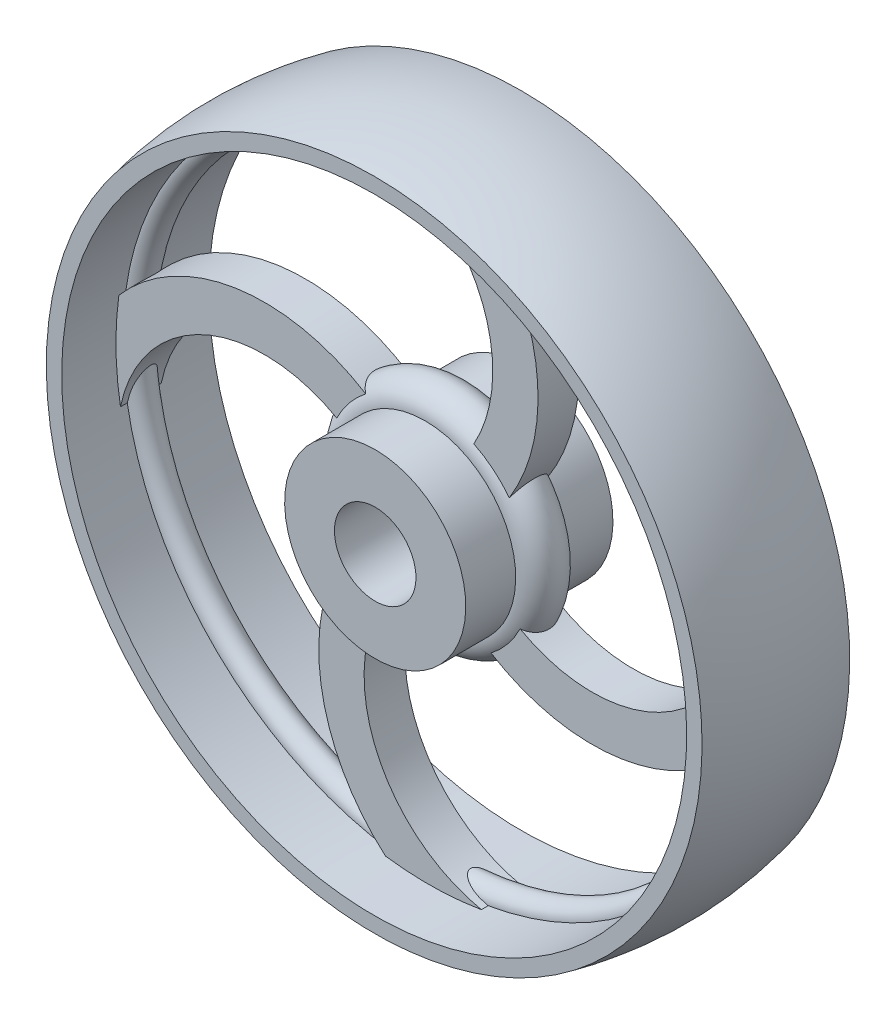
SolidWorks part; units mm, degrees
ref_plane "Front Plane" through (0, 0, 0) normal (0, 0, 1) x (1, 0, 0)
ref_plane "Top Plane" through (0, 0, 0) normal (0, 1, 0) x (1, 0, 0)
ref_plane "Right Plane" through (0, 0, 0) normal (1, 0, 0) x (0, 0, -1)
sketch "Sketch1" plane through (0, 0, 0) normal (0, 0, 1) x (1, 0, 0)
  circle A0 centre (0, 0) radius 145
  dimension "D1" = 290
sketch "Sketch2" plane through (0, 0, 0) normal (1, 0, 0) x (0, 0, -1)
  line L0 (5.9992, 138) -> (32.0507, 138)
  line L2 (-32.9493, 144.7985) -> (-32.9493, 138)
  line L3 (-32.9493, 138) -> (-5.9992, 138)
  line L4 (32.0507, 145) -> (32.0507, 138)
  line L5 (-54.2193, 131.9) -> (55.8258, 131.9) construction
  arc A0 (32.0507, 145) -> (-32.9493, 144.7985) centre (0, 0) ccw
  arc A2 (-5.9992, 138) -> (5.9992, 138) centre (0, 137.9) ccw
  dimension "D3" = 297
  dimension "D4" = 6
  dimension "D5" = 5.9992
  dimension "D1" = 145
  dimension "D2" = 65
  dimension "D6" = 131.9
sweep "Sweep1" add profiles "Sketch2" path "Sketch1"
sketch "Sketch3" plane through (0, 0, 0) normal (0, 0, 1) x (1, 0, 0)
  circle A0 centre (0, 0) radius 40
  dimension "D1" = 80
sketch "Sketch4" plane through (0, 0, 0) normal (1, 0, 0) x (0, 0, -1)
  line L0 (0, 40) -> (0, -40) construction
  line L1 (-32.5, 40) -> (-10.4493, 40)
  line L2 (-32.5, 40) -> (-32.5, 18)
  line L3 (-32.5, 18) -> (32.5, 18)
  line L4 (32.5, 40) -> (32.5, 18)
  line L5 (-32.5, 40) -> (32.5, 18) construction
  line L6 (-32.5, 18) -> (32.5, 40) construction
  line L7 (-75.8881, 50) -> (78.6581, 50) construction
  line L8 (9.5507, 40) -> (32.5, 40)
  line L9 (-32.9493, 144.7985) -> (-32.9493, -144.7985) construction
  arc A1 (9.5507, 40) -> (-10.4493, 40) centre (-0.4493, 40) ccw
  point P0 (0, 29)
  dimension "D3" = 22
  dimension "D5" = 10
  dimension "D6" = 32.5
  dimension "D1" = 40
  dimension "D2" = 50
  dimension "D4" = 65
sweep "Sweep2" add profiles "Sketch4" path "Sketch3"
sketch "Sketch10" plane through (0, 0, 0) normal (0, 0, 1) x (1, 0, 0)
  line L0 (0, 0) -> (0, 189.5926) construction
  arc A0 (17.3304, 36.0508) -> (-23.394, 136.0026) centre (-36.586, 72.3554) ccw
  circle A1 centre (0, 0) radius 40 construction
  circle A2 centre (0, 0) radius 138 construction
  arc A3 (32.6719, 23.077) -> (18.9657, 136.6905) centre (-36.586, 72.3554) ccw
  circle A4 centre (0, 0) radius 40 construction
  circle A5 centre (0, 0) radius 138 construction
  arc A6 (-23.394, 136.0026) -> (18.9657, 136.6905) centre (0, 0) cw
  arc A7 (17.3304, 36.0508) -> (32.6719, 23.077) centre (0, 0) cw
  dimension "D1" = 65
  dimension "D2" = 85
  dimension "D3" = 17.3304
  dimension "D4" = 18.9657
extrude "Boss-Extrude3" add sketch "Sketch10" along normal mid plane 18
pattern_circular "CirPattern1" count 4 over 360 about axis through (0, 0, 0) along (0, 0, 1) of "Boss-Extrude3"
